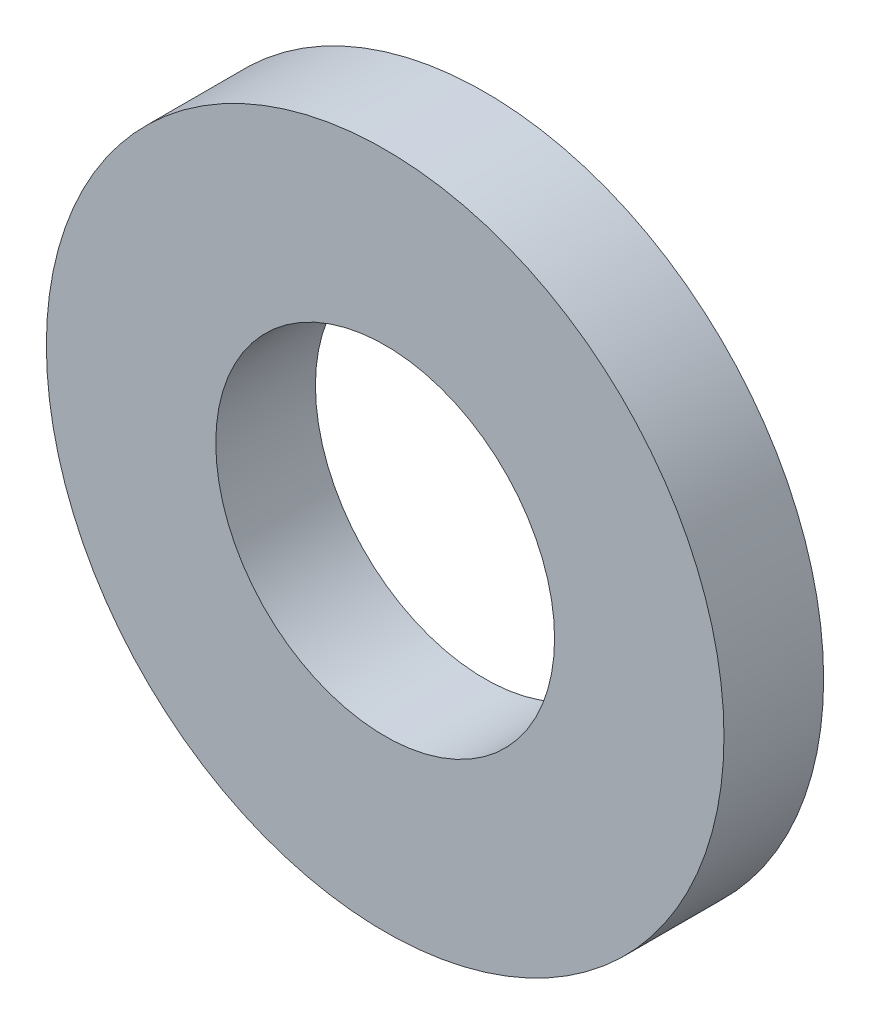
SolidWorks part; units mm, degrees
ref_plane "Front Plane" through (0, 0, 0) normal (0, 0, 1) x (1, 0, 0)
ref_plane "Top Plane" through (0, 0, 0) normal (0, 1, 0) x (1, 0, 0)
ref_plane "Right Plane" through (0, 0, 0) normal (1, 0, 0) x (0, 0, -1)
sketch "Эскиз1" plane through (0, 0, 0) normal (0, 0, 1) x (1, 0, 0)
  circle A0 centre (0, 0) radius 34
  circle A1 centre (0, 0) radius 17
extrude "Бобышка-Вытянуть1" add sketch "Эскиз1" along normal blind 10
